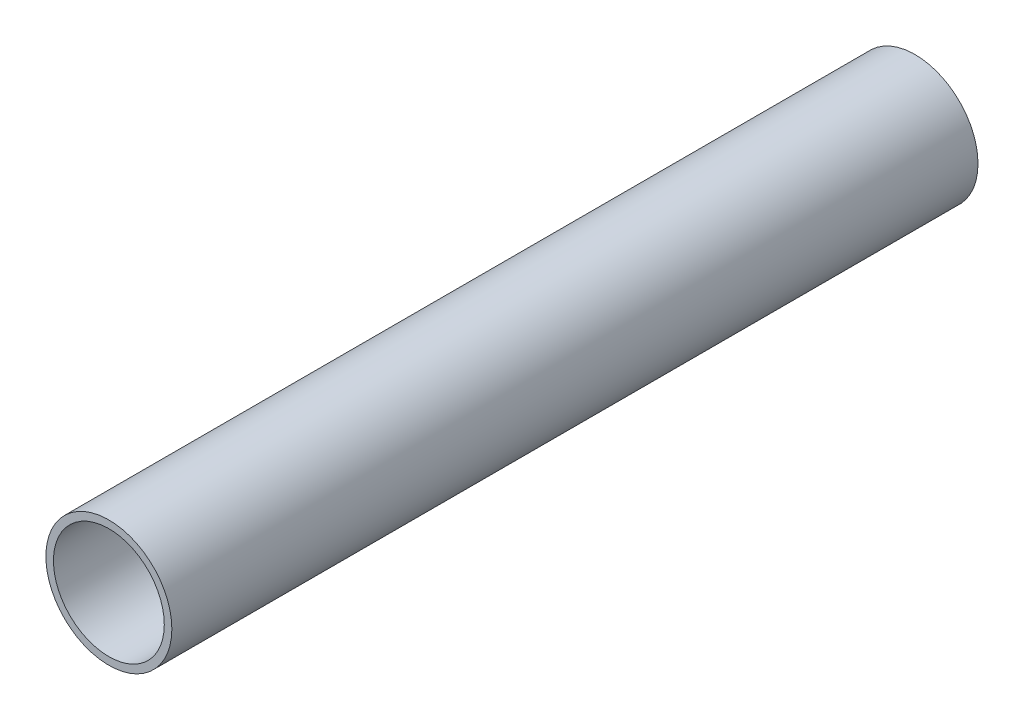
SolidWorks part; units mm, degrees
ref_plane "Front Plane" through (0, 0, 0) normal (0, 0, 1) x (1, 0, 0)
ref_plane "Top Plane" through (0, 0, 0) normal (0, 1, 0) x (1, 0, 0)
ref_plane "Right Plane" through (0, 0, 0) normal (1, 0, 0) x (0, 0, -1)
sketch "Sketch5" plane through (0, 0, 0) normal (0, 0, 1) x (1, 0, 0)
  circle A0 centre (0, 0) radius 63.5042
  circle A1 centre (0, 0) radius 55.88
extrude "Boss-Extrude1" add sketch "Sketch5" along normal blind 812.8
